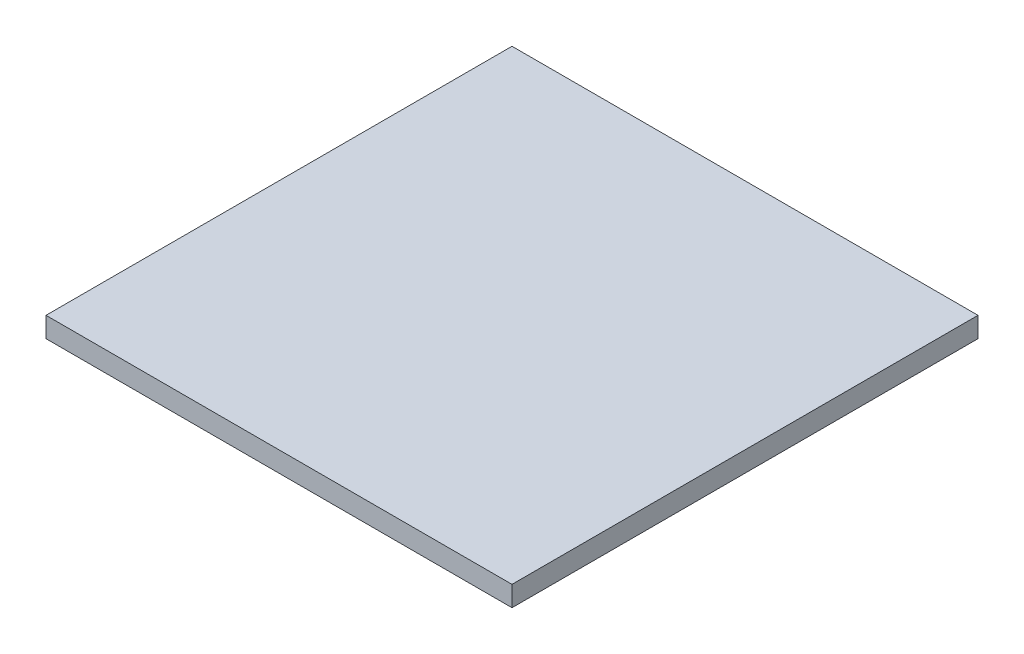
SolidWorks part; units mm, degrees
material "1060 Alloy"
ref_plane "Front Plane" through (0, 0, 0) normal (0, 0, 1) x (1, 0, 0)
ref_plane "Top Plane" through (0, 0, 0) normal (0, 1, 0) x (1, 0, 0)
ref_plane "Right Plane" through (0, 0, 0) normal (1, 0, 0) x (0, 0, -1)
sketch "Sketch1" plane through (0, 0, 0) normal (0, 1, 0) x (1, 0, 0)
  line L1 (-46, -46) -> (46, -46)
  line L2 (-46, -46) -> (-46, 46)
  line L3 (-46, 46) -> (46, 46)
  line L4 (46, -46) -> (46, 46)
  line L5 (-46, -46) -> (46, 46) construction
  line L6 (-46, 46) -> (46, -46) construction
  point P0 (0, 0)
  dimension "D1" = 92
  dimension "D2" = 92
extrude "Boss-Extrude1" add sketch "Sketch1" along normal blind 4
sketch "Sketch2" plane through (0, 4, 0) normal (0, 1, 0) x (1, 0, 0)
  line L1 (-19, -19) -> (19, -19)
  line L2 (-19, -19) -> (-19, 19)
  line L3 (-19, 19) -> (19, 19)
  line L4 (19, -19) -> (19, 19)
  line L5 (-19, -19) -> (19, 19) construction
  line L6 (-19, 19) -> (19, -19) construction
  point P0 (0, 0)
  dimension "D1" = 38
